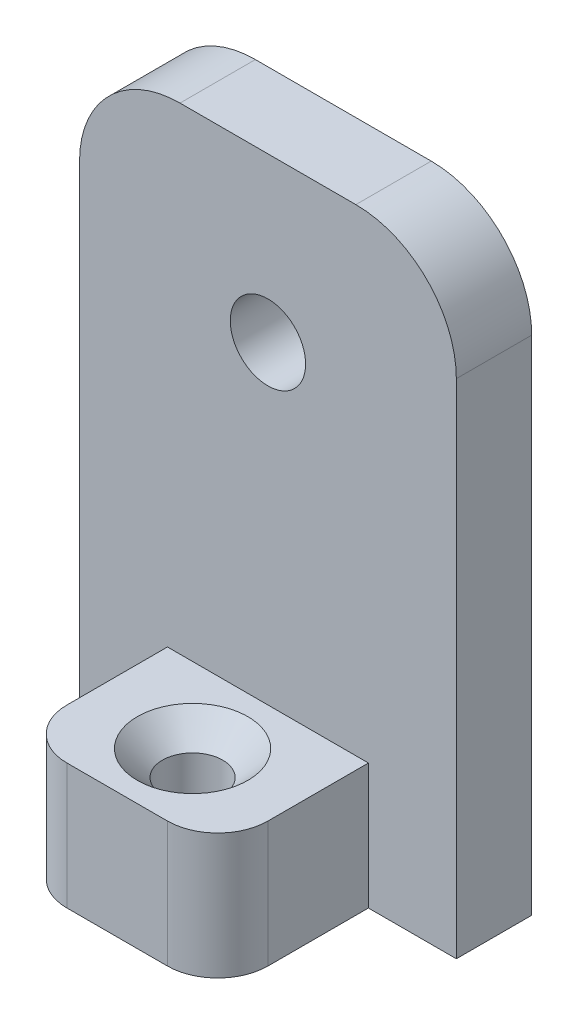
SolidWorks part; units mm, degrees
material "Mahogany"
ref_plane "Front Plane" through (0, 0, 0) normal (0, 0, 1) x (1, 0, 0)
ref_plane "Top Plane" through (0, 0, 0) normal (0, 1, 0) x (1, 0, 0)
ref_plane "Right Plane" through (0, 0, 0) normal (1, 0, 0) x (0, 0, -1)
sketch "Sketch1" plane through (0, 0, 0) normal (0, 0, 1) x (1, 0, 0)
  line L1 (-7.5, -12) -> (7.5, -12)
  line L2 (-7.5, -12) -> (-7.5, 12)
  line L3 (-7.5, 12) -> (7.5, 12)
  line L4 (7.5, -12) -> (7.5, 12)
  line L5 (-7.5, -12) -> (7.5, 12) construction
  line L6 (-7.5, 12) -> (7.5, -12) construction
  point P0 (0, 0)
  dimension "D1" = 15
  dimension "D2" = 24
extrude "Boss-Extrude1" add sketch "Sketch1" along normal blind 3
sketch "Sketch2" plane through (0, 0, 3) normal (0, 0, 1) x (1, 0, 0)
  line L0 (-7.5, -12) -> (7.5, -12) construction
  line L1 (-4, -12) -> (4, -12)
  line L2 (-4, -12) -> (-4, -7)
  line L3 (-4, -7) -> (4, -7)
  line L4 (4, -12) -> (4, -7)
  line L5 (-7.5, 12) -> (-7.5, -12) construction
  line L6 (7.5, -12) -> (7.5, 12) construction
  dimension "D1" = 3.5
  dimension "D2" = 3.5
  dimension "D3" = 5
extrude "Boss-Extrude2" add sketch "Sketch2" along normal blind 6
sketch "Sketch3" plane through (0, -7, 0) normal (0, 1, 0) x (1, 0, 0)
  line L0 (4, -3) -> (-4, -3) construction
  line L2 (4, -9) -> (4, -3) construction
  circle A0 centre (0, -6) radius 1.5
  dimension "D3" = 3
  dimension "D1" = 3
  dimension "D2" = 4
hole_wizard "CSK for M2 Flat Head Machine Screw1" positions "3DSketch1" profile "Sketch4" countersink size "M2" standard "ANSI Metric"
sketch3d "3DSketch1"
  point P0 (0, -7, 6)
sketch "Sketch4" plane through (0, -7, 6) normal (1, 0, 0) x (0, 0, 1)
  line L0 (0, 0) -> (0, 5.72)
  line L1 (0, 5.72) -> (1.2, 4.999)
  line L2 (1.2, 4.999) -> (1.2, 1)
  line L3 (1.2, 1) -> (2.2, 0)
  line L5 (2.2, 0) -> (0, 0)
  line L6 (-1.2, 1) -> (-2.2, 0) construction
  line L10 (0, 5.72) -> (-1.2, 4.999) construction
  line L11 (0, -6.35) -> (0, 107.95) construction
  dimension "Hole Dia." = 2.4
  dimension "Hole Depth" = 4.999
  dimension "Near C'Sink Dia." = 4.4
  dimension "Near C'Sink Angle" = 90
  dimension "Drill Angle" = 118
fillet "Fillet1" radius 2 2 edges at (4, -9.5, 9) (-4, -9.5, 9)
sketch "Sketch5" plane through (0, 0, 0) normal (0, 0, -1) x (-1, 0, 0)
  line L1 (-7.5, -12) -> (-7.5, 12) construction
  line L2 (7.5, -12) -> (-7.5, -12) construction
  circle A0 centre (0, 5.5) radius 1.5
  dimension "D3" = 3
  dimension "D4" = 17.5
  dimension "D2" = 7.5
extrude "Cut-Extrude1" cut sketch "Sketch5" against normal up to surface (3 mm away) up to face at (0, -4.75, 3)
fillet "Fillet2" radius 4 2 edges at (-7.5, 12, 1.5) (7.5, 12, 1.5)
